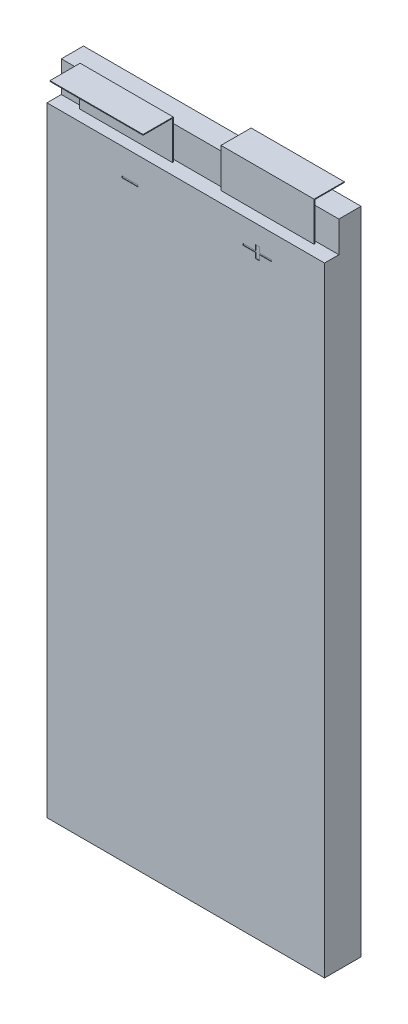
SolidWorks part; units mm, degrees
ref_plane "前视基准面" through (0, 0, 0) normal (0, 0, 1) x (1, 0, 0)
ref_plane "上视基准面" through (0, 0, 0) normal (0, 1, 0) x (1, 0, 0)
ref_plane "右视基准面" through (0, 0, 0) normal (1, 0, 0) x (0, 0, -1)
sketch "草图1" plane through (0, 0, 0) normal (0, 0, 1) x (1, 0, 0)
  line L1 (37.25, -83.1) -> (-37.25, -83.1)
  line L2 (37.25, -83.1) -> (37.25, 83.1)
  line L3 (37.25, 83.1) -> (-37.25, 83.1)
  line L4 (-37.25, -83.1) -> (-37.25, 83.1)
  line L5 (37.25, -83.1) -> (-37.25, 83.1) construction
  line L6 (37.25, 83.1) -> (-37.25, -83.1) construction
  point P0 (0, 0)
  dimension "D1" = 166.2
  dimension "D2" = 74.5
extrude "凸台-拉伸1" add sketch "草图1" along normal mid plane 9.8
sketch "草图3" plane through (0, 83.1, 0) normal (0, 1, 0) x (1, 0, 0)
  line L0 (37.25, -4.9) -> (37.25, 4.9) construction
  line L1 (-37.25, 4.9) -> (37.25, 4.9)
  line L2 (-37.25, 4.9) -> (-37.25, -1.05)
  line L3 (-37.25, -1.05) -> (37.25, -1.05)
  line L4 (37.25, 4.9) -> (37.25, -1.05)
  dimension "D1" = 5.95
extrude "凸台-拉伸2" add sketch "草图3" along normal blind 8.3
sketch "草图4" plane through (0, 83.1, 0) normal (0, 1, 0) x (1, 0, 0)
  line L0 (0, 0) -> (0, -15.0902) construction
  line L1 (-6.5, -1.95) -> (-31.5, -1.95)
  line L2 (-6.5, -1.95) -> (-6.5, -1.75)
  line L3 (-6.5, -1.75) -> (-31.5, -1.75)
  line L4 (-31.5, -1.95) -> (-31.5, -1.75)
  line L5 (-6.5, -1.95) -> (-31.5, -1.75) construction
  line L6 (-6.5, -1.75) -> (-31.5, -1.95) construction
  line L7 (6.5, -1.75) -> (31.5, -1.95) construction
  line L8 (6.5, -1.95) -> (31.5, -1.75) construction
  line L9 (31.5, -1.95) -> (31.5, -1.75)
  line L10 (6.5, -1.75) -> (31.5, -1.75)
  line L11 (6.5, -1.95) -> (6.5, -1.75)
  line L12 (6.5, -1.95) -> (31.5, -1.95)
  line L13 (37.25, -4.9) -> (-37.25, -4.9) construction
  point P0 (-19, -1.85)
  point P12 (19, -1.85)
  dimension "D1" = 0.2
  dimension "D2" = 2.95
  dimension "D3" = 19
  dimension "D4" = 25
extrude "凸台-拉伸4" add sketch "草图4" along normal blind 10.5
sketch "草图6" plane through (0, 0, 1.95) normal (0, 0, 1) x (1, 0, 0)
  line L0 (-6.5, 93.6) -> (-6.5, 83.1) construction
  line L1 (-31.5, 93.6) -> (-6.5, 93.6)
  line L2 (-31.5, 93.6) -> (-31.5, 93.4)
  line L3 (-31.5, 93.4) -> (-6.5, 93.4)
  line L4 (-6.5, 93.6) -> (-6.5, 93.4)
  dimension "D1" = 0.2
extrude "凸台-拉伸5" add sketch "草图6" along normal blind 7.9
sketch "草图7" plane through (0, 0, 1.75) normal (0, 0, -1) x (-1, 0, 0)
  line L0 (-6.5, 93.6) -> (-6.5, 83.1) construction
  line L1 (-31.5, 93.6) -> (-6.5, 93.6)
  line L2 (-31.5, 93.6) -> (-31.5, 93.4)
  line L3 (-31.5, 93.4) -> (-6.5, 93.4)
  line L4 (-6.5, 93.6) -> (-6.5, 93.4)
  dimension "D1" = 0.2
extrude "凸台-拉伸6" add sketch "草图7" along normal blind 7.9
sketch "草图8" plane through (0, 0, -4.9) normal (0, 0, -1) x (-1, 0, 0)
  line L0 (-30.1314, 74.1565) -> (29.7533, 74.1565) construction
  text T0 " +    -" font "Century Gothic" height in points 18
extrude "切除-拉伸1" cut sketch "草图8" against normal blind 0.1
mirror "镜向1" about plane through (0, 0, 0) normal (0, 0, 1) of "切除-拉伸1"
